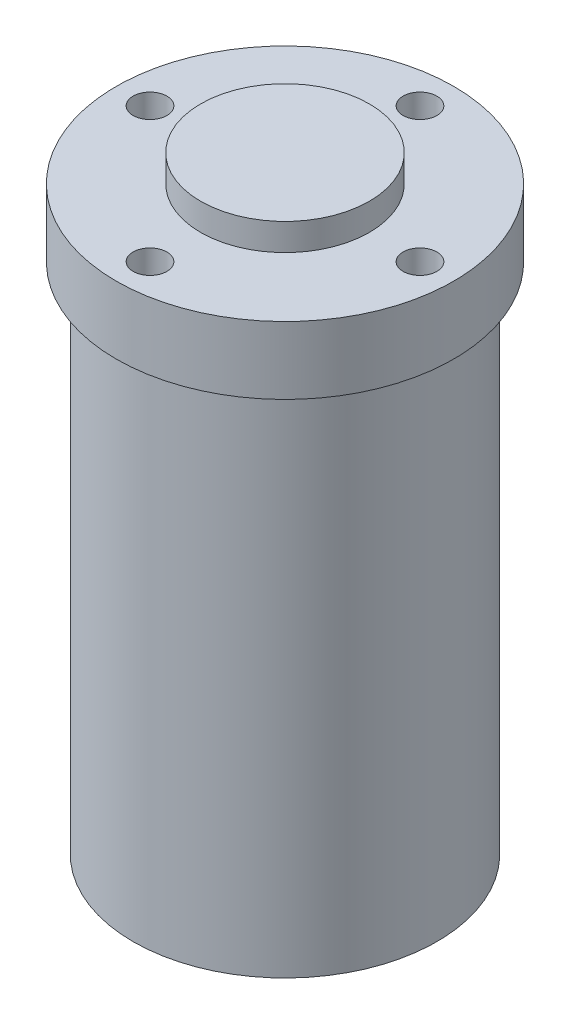
SolidWorks part; units mm, degrees
material "ASTM A36 Steel"
ref_plane "Front Plane" through (0, 0, 0) normal (0, 0, 1) x (1, 0, 0)
ref_plane "Top Plane" through (0, 0, 0) normal (0, 1, 0) x (1, 0, 0)
ref_plane "Right Plane" through (0, 0, 0) normal (1, 0, 0) x (0, 0, -1)
sketch "Sketch1" plane through (0, 0, 0) normal (0, 1, 0) x (1, 0, 0)
  circle A0 centre (0, 0) radius 22.5
  dimension "D1" = 45
extrude "Boss-Extrude1" add sketch "Sketch1" along normal blind 76
sketch "Sketch2" plane through (0, 76, 0) normal (0, 1, 0) x (1, 0, 0)
  circle A0 centre (0, 0) radius 25
  dimension "D1" = 50
extrude "Boss-Extrude2" add sketch "Sketch2" along normal blind 10
sketch "Sketch3" plane through (0, 86, 0) normal (0, 1, 0) x (1, 0, 0)
  circle A0 centre (0, 0) radius 12.5
  dimension "D1" = 25
extrude "Boss-Extrude3" add sketch "Sketch3" along normal blind 4
sketch "Sketch4" plane through (0, 86, 0) normal (0, 1, 0) x (1, 0, 0)
  circle A0 centre (-20, 0) radius 2.5
  dimension "D1" = 5
  dimension "D2" = 20
extrude "Cut-Extrude1" cut sketch "Sketch4" against normal blind 8
pattern_circular "CirPattern1" count 4 over 360 about axis through (0, 0, 0) along (0, 1, 0) of "Cut-Extrude1"
sketch "Sketch5" plane through (0, 0, 0) normal (0, -1, 0) x (1, 0, 0)
  circle A0 centre (0, 17.5) radius 2.5
  dimension "D1" = 5
  dimension "D2" = 17.5
extrude "Cut-Extrude2" cut sketch "Sketch5" against normal blind 8
pattern_circular "CirPattern2" count 5 over 360 about axis through (0, 0, 0) along (0, 1, 0) of "Cut-Extrude2"
